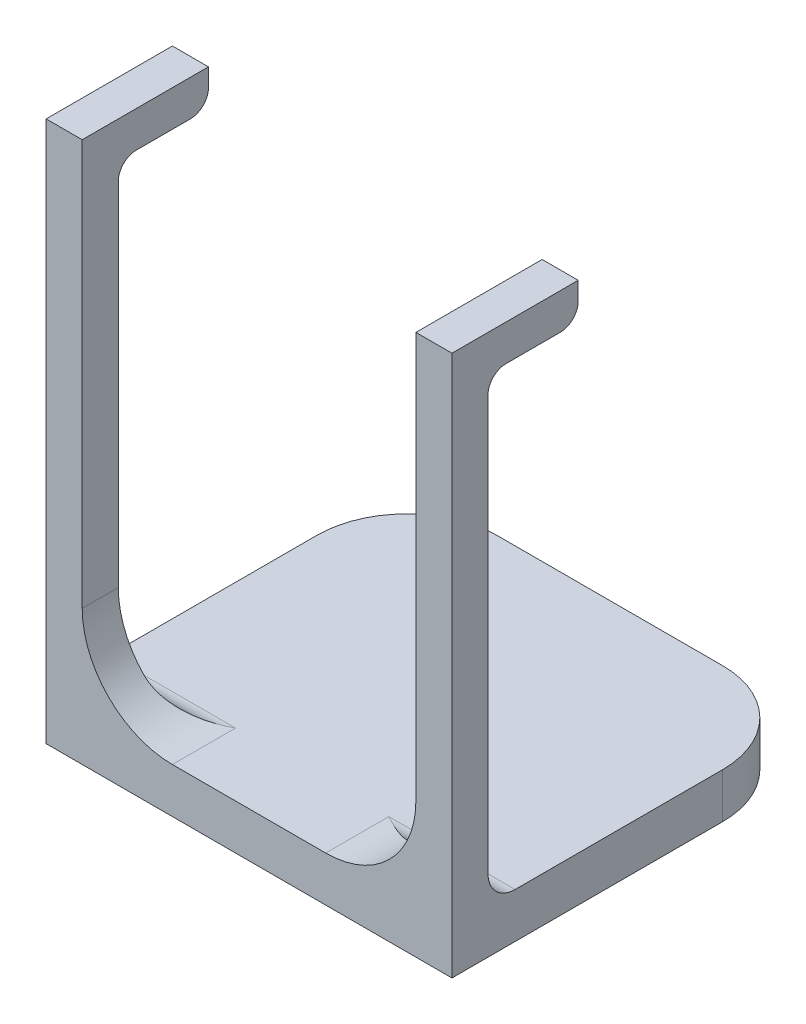
SolidWorks part; units mm, degrees
ref_plane "Front Plane" through (0, 0, 0) normal (0, 0, 1) x (1, 0, 0)
ref_plane "Top Plane" through (0, 0, 0) normal (0, 1, 0) x (1, 0, 0)
ref_plane "Right Plane" through (0, 0, 0) normal (1, 0, 0) x (0, 0, -1)
sketch "Sketch1" plane through (0, 0, 0) normal (0, 1, 0) x (1, 0, 0)
  line L1 (22.5, -20) -> (-22.5, -20)
  line L2 (22.5, -20) -> (22.5, 20)
  line L3 (22.5, 20) -> (-22.5, 20)
  line L4 (-22.5, -20) -> (-22.5, 20)
  line L5 (22.5, -20) -> (-22.5, 20) construction
  line L6 (22.5, 20) -> (-22.5, -20) construction
  point P0 (0, 0)
  dimension "D1" = 45
  dimension "D2" = 40
extrude "Boss-Extrude1" add sketch "Sketch1" along normal blind 5
sketch "Sketch2" plane through (0, 0, 0) normal (0, -1, 0) x (-1, 0, 0)
  circle A0 centre (0, 0) radius 12.7
  dimension "D1" = 25.4
extrude "Cut-Extrude1" cut sketch "Sketch2" against normal blind 3.2
sketch "Sketch3" plane through (0, 5, 0) normal (0, 1, 0) x (1, 0, 0)
  line L0 (-22.5, -20) -> (22.5, -20) construction
  line L1 (-22.5, -20) -> (-18.5, -20)
  line L2 (-22.5, -20) -> (-22.5, -16)
  line L3 (-22.5, -16) -> (-18.5, -16)
  line L4 (-18.5, -20) -> (-18.5, -16)
  line L5 (18.5, -20) -> (22.5, -20)
  line L6 (18.5, -20) -> (18.5, -16)
  line L7 (18.5, -16) -> (22.5, -16)
  line L8 (22.5, -20) -> (22.5, -16)
  dimension "D1" = 4
  dimension "D2" = 4
  dimension "D3" = 4
  dimension "D4" = 37
extrude "Boss-Extrude2" add sketch "Sketch3" along normal blind 55
sketch "Sketch4" plane through (0, 0, 16) normal (0, 0, -1) x (-1, 0, 0)
  line L0 (18.5, 60) -> (18.5, 5) construction
  line L1 (22.5, 60) -> (18.5, 60)
  line L2 (22.5, 60) -> (22.5, 56)
  line L3 (22.5, 56) -> (18.5, 56)
  line L4 (18.5, 60) -> (18.5, 56)
  line L5 (-18.5, 60) -> (-18.5, 5) construction
  line L6 (-22.5, 60) -> (-18.5, 60)
  line L7 (-22.5, 60) -> (-22.5, 56)
  line L8 (-22.5, 56) -> (-18.5, 56)
  line L9 (-18.5, 60) -> (-18.5, 56)
  dimension "D1" = 4
extrude "Boss-Extrude3" add sketch "Sketch4" along normal blind 10
fillet "Fillet1" radius 10 2 edges at (18.5, 5, 18) (-18.5, 5, 18)
fillet "Fillet2" radius 2 4 edges at (20.5, 56, 16) (-20.5, 56, 16) (20.5, 56, 6) (-20.5, 56, 6)
fillet "Fillet3" radius 3 2 edges at (-15.5, 5, 16) (15.5, 5, 16)
fillet "Fillet4" radius 10 2 edges at (-22.5, 2.5, -20) (22.5, 2.5, -20)
equation "\"depth\"=55"
equation "\"D1@Boss-Extrude2\"=\"depth\""
